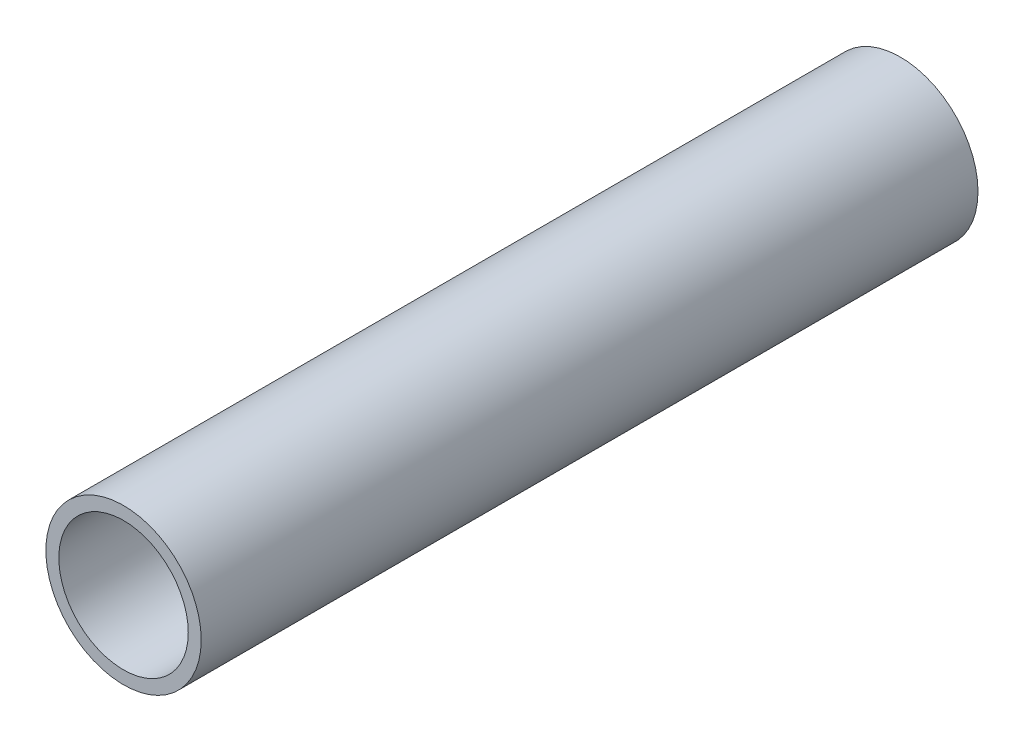
SolidWorks part; units mm, degrees
ref_plane "前视基准面" through (0, 0, 0) normal (0, 0, 1) x (1, 0, 0)
ref_plane "上视基准面" through (0, 0, 0) normal (0, 1, 0) x (1, 0, 0)
ref_plane "右视基准面" through (0, 0, 0) normal (1, 0, 0) x (0, 0, -1)
sketch "Sketch1" plane through (0, 0, 0) normal (0, 0, 1) x (1, 0, 0)
  circle A0 centre (0, 0) radius 3
  circle A1 centre (0, 0) radius 2.5
  dimension "D1" = 6
  dimension "D2" = 5
extrude "Boss-Extrude1" add sketch "Sketch1" along normal blind 30
